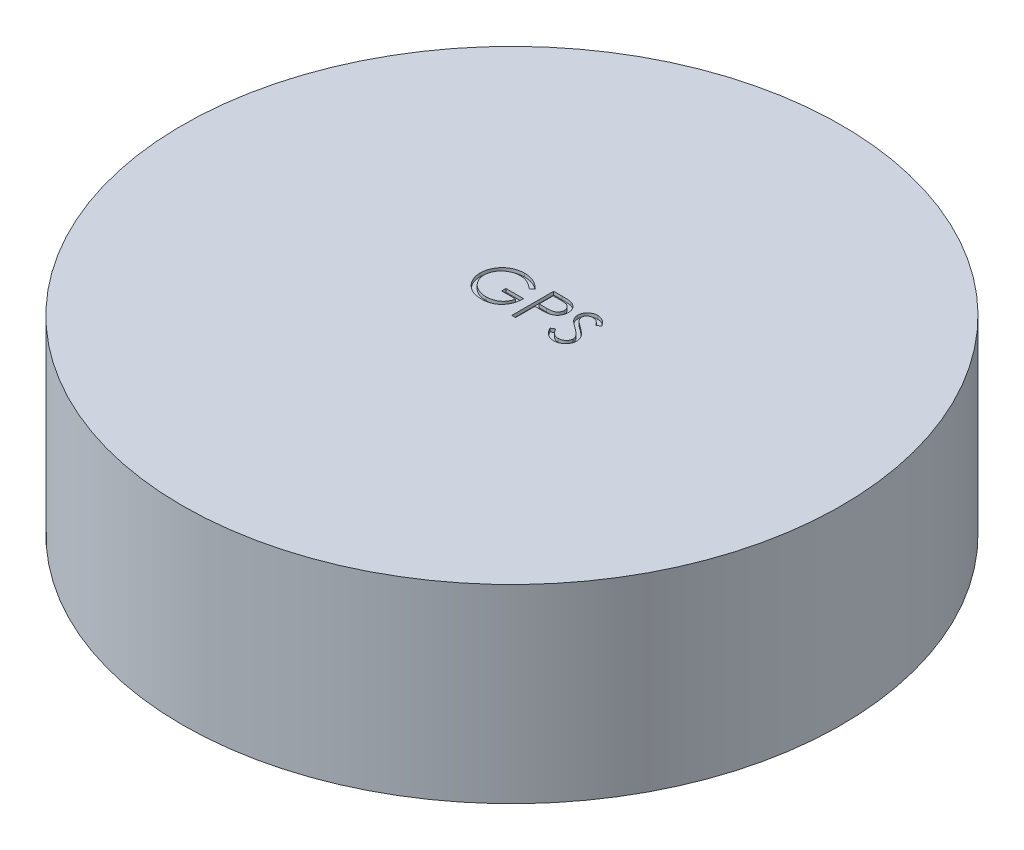
SolidWorks part; units mm, degrees
ref_plane "Front Plane" through (0, 0, 0) normal (0, 0, 1) x (1, 0, 0)
ref_plane "Top Plane" through (0, 0, 0) normal (0, 1, 0) x (1, 0, 0)
ref_plane "Right Plane" through (0, 0, 0) normal (1, 0, 0) x (0, 0, -1)
sketch "Sketch1" plane through (0, 0, 0) normal (0, 1, 0) x (1, 0, 0)
  circle A0 centre (0, 0) radius 25
  dimension "D1" = 50
extrude "Boss-Extrude1" add sketch "Sketch1" along normal blind 14.4
sketch "Sketch2" plane through (0, 14.4, 0) normal (0, 1, 0) x (1, 0, 0)
  line L0 (-25, 0) -> (25, 0) construction
  circle A0 centre (0, 0) radius 25 construction
  text T0 "                 GPS"
extrude "Cut-Extrude1" cut sketch "Sketch2" against normal blind 0.254
